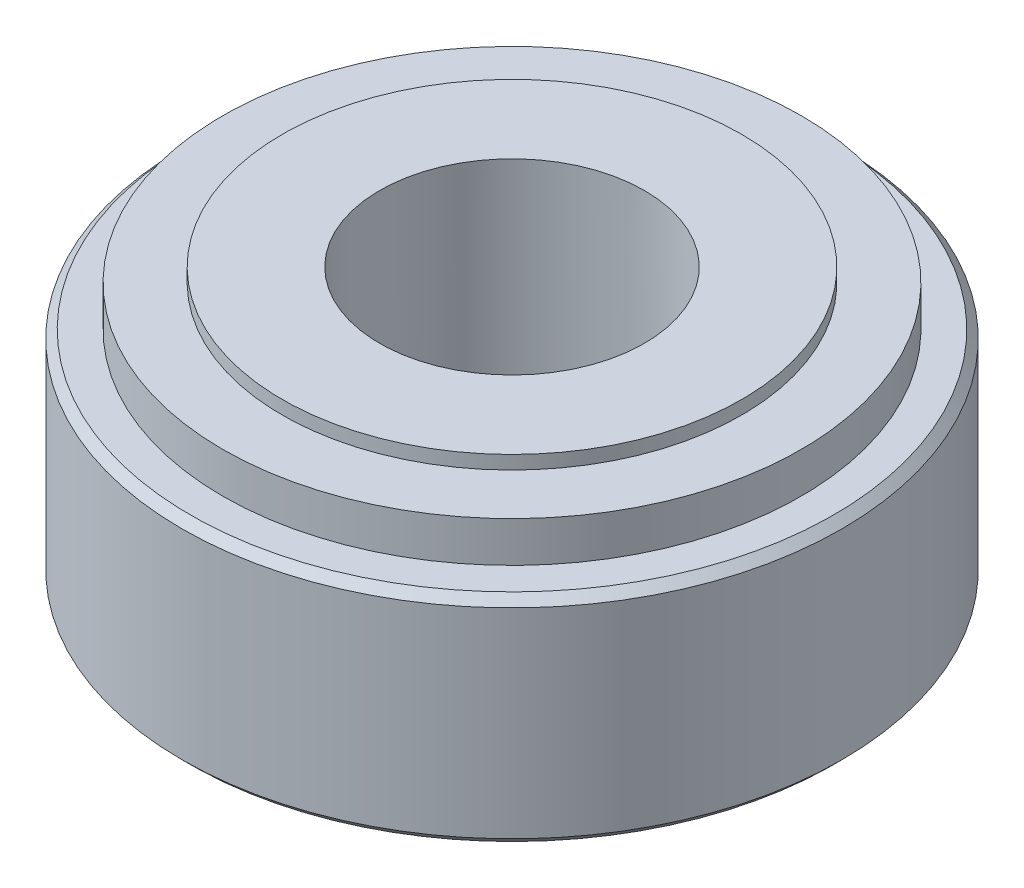
SolidWorks part; units mm, degrees
ref_plane "Płaszczyzna przednia" through (0, 0, 0) normal (0, 0, 1) x (1, 0, 0)
ref_plane "Płaszczyzna górna" through (0, 0, 0) normal (0, 1, 0) x (1, 0, 0)
ref_plane "Płaszczyzna prawa" through (0, 0, 0) normal (1, 0, 0) x (0, 0, -1)
sketch "Szkic1" plane through (0, 0, 0) normal (0, 0, 1) x (1, 0, 0)
  line L0 (0, 0) -> (0, 92.7865) construction
  line L1 (-49, 89.8156) -> (-49, 0) construction
  line L2 (-122, -10.1844) -> (-122, 70.0729)
  line L5 (-49, 89.8156) -> (-50.7455, -10.1844)
  line L6 (-50.7455, -10.1844) -> (-122, -10.1844)
  line L7 (-107, 84.8156) -> (-107, 69.8156)
  line L8 (-107, 69.8156) -> (-122, 69.8156)
  line L9 (-122, 69.8156) -> (-122, 70.0729)
  line L10 (-107, 69.8156) -> (-107, 84.8156)
  line L11 (-107, 84.8156) -> (-85, 84.8156)
  line L12 (-85, 84.8156) -> (-85, 89.8156)
  line L13 (-85, 89.8156) -> (-49, 89.8156)
  dimension "D1" = 122
  dimension "D2" = 1
  dimension "D3" = 49
  dimension "D4" = 100
  dimension "D5" = 107
  dimension "D6" = 80
  dimension "D7" = 85
revolve "Obrót1" add sketch "Szkic1" angle 360 about L0
chamfer "Sfazowanie2" distance 3 angle 45 2 edges at (0, -10.1844, -122) (0, 69.8156, -122)
